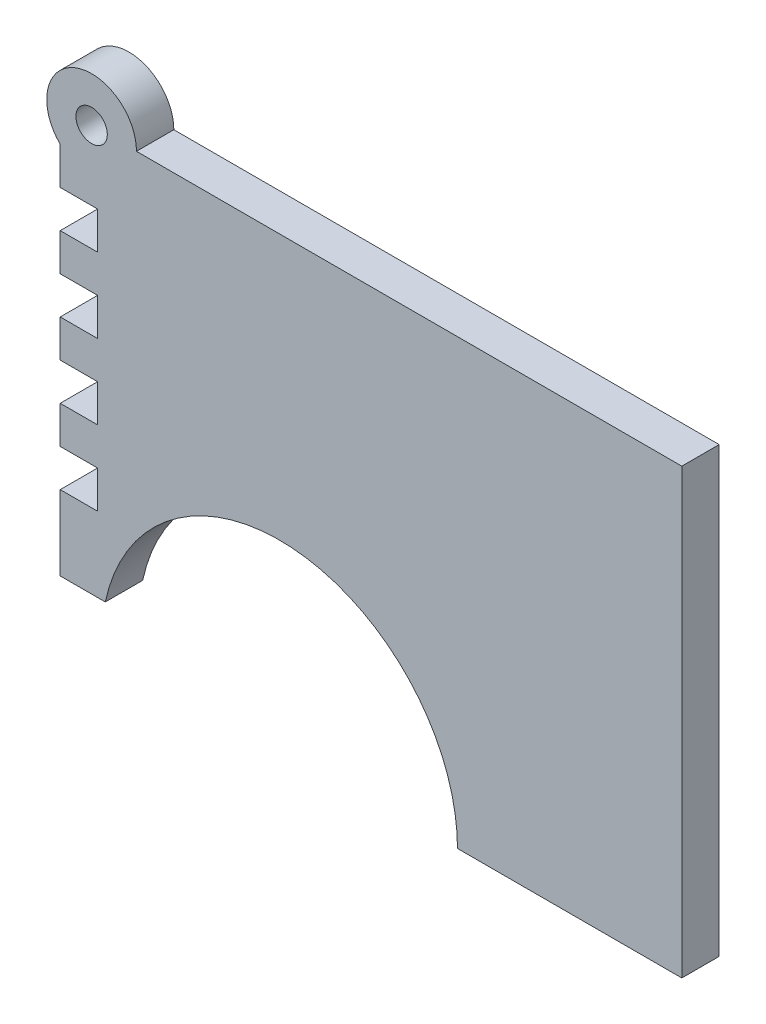
SolidWorks part; units mm, degrees
ref_plane "Plan de face" through (0, 0, 0) normal (0, 0, 1) x (1, 0, 0)
ref_plane "Plan de dessus" through (0, 0, 0) normal (0, 1, 0) x (1, 0, 0)
ref_plane "Plan de droite" through (0, 0, 0) normal (1, 0, 0) x (0, 0, -1)
sketch "Esquisse1" plane through (0, 0, 0) normal (0, 0, 1) x (1, 0, 0)
  line L2 (-78.1359, 18.8424) -> (-83.1359, 18.8424)
  line L3 (-78.1359, 13.8424) -> (-78.1359, 18.8424)
  line L4 (-83.1359, 13.8424) -> (-78.1359, 13.8424)
  line L5 (-83.1359, 8.8424) -> (-83.1359, 13.8424)
  line L6 (-78.1359, 8.8424) -> (-83.1359, 8.8424)
  line L7 (-78.1359, 3.8424) -> (-78.1359, 8.8424)
  line L8 (-83.1359, 3.8424) -> (-78.1359, 3.8424)
  line L9 (-83.1359, -1.1576) -> (-83.1359, 3.8424)
  line L10 (-78.1359, -1.1576) -> (-83.1359, -1.1576)
  line L11 (-78.1359, -1.1576) -> (-78.1359, -6.1576)
  line L12 (-83.1359, -6.1576) -> (-78.1359, -6.1576)
  line L19 (0, 13.8424) -> (0, -31.1576)
  line L21 (0, -5.7761) -> (-55, -5.7761) construction
  line L22 (-77.6359, -31.1576) -> (-30, -31.1576) construction
  line L23 (0, -31.1576) -> (-30, -31.1576)
  line L25 (-83.1359, -11.1576) -> (-78.1359, -11.1576)
  line L26 (-78.1359, -11.1576) -> (-78.1359, -16.1576)
  line L27 (-78.1359, -16.1576) -> (-83.1359, -16.1576)
  line L34 (-83.1359, -6.1576) -> (-83.1359, -11.1576)
  line L37 (-83.1359, 23.8434) -> (-83.1359, 18.8424)
  line L42 (0, 13.8424) -> (0, 28.1282)
  line L45 (-77.1052, -26.1576) -> (-83.1359, -26.1576)
  line L46 (-83.1359, -16.1576) -> (-83.1359, -26.1576)
  line L48 (0, 28.1282) -> (-72.9359, 28.1282)
  circle A6 centre (-78.9359, 28.1282) radius 2.1
  arc A7 (-30, -31.1576) -> (-77.1052, -26.1576) centre (-53.8179, -31.1576) ccw
  arc A9 (-72.9359, 28.1282) -> (-83.1359, 32.4131) centre (-78.9359, 28.1282) ccw
  arc A10 (-83.1359, 32.4131) -> (-83.1359, 23.8434) centre (-78.9359, 28.1282) ccw
  dimension "D2" = 30
  dimension "D5" = 6
  dimension "D1" = 4.2
  dimension "D3" = 45
  dimension "D6" = 5
  dimension "D8" = 5
extrude "Boss.-Extru.1" add sketch "Esquisse1" along normal blind 5
